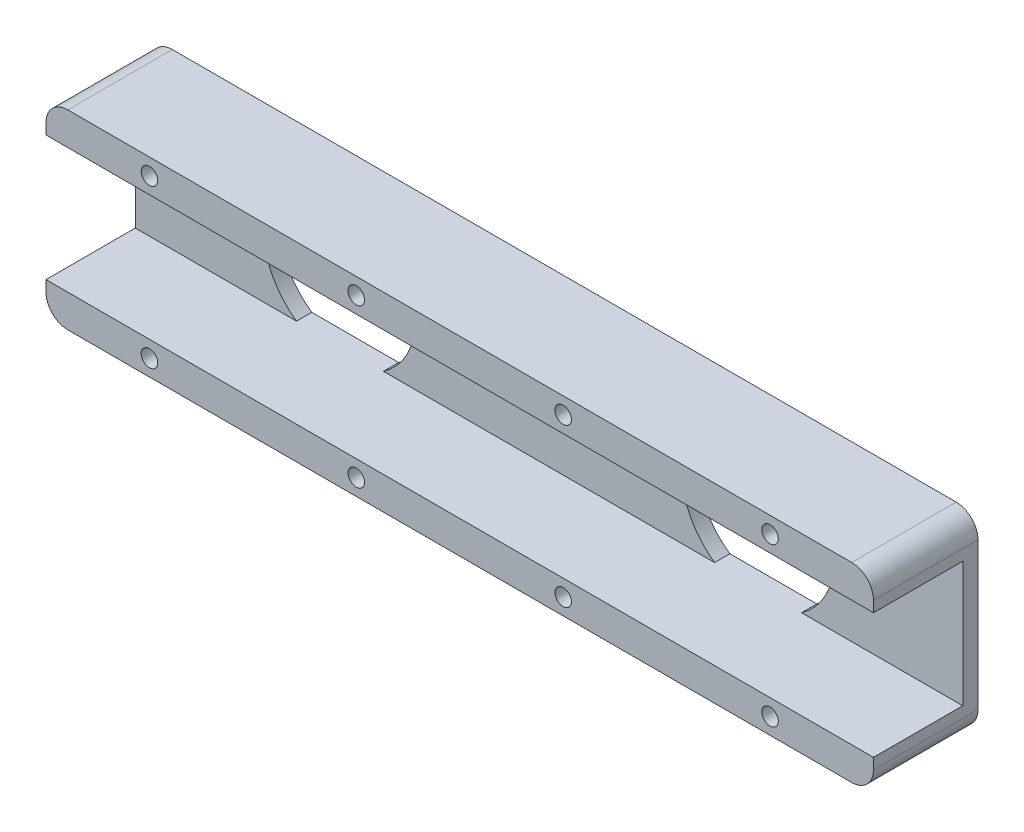
SolidWorks part; units mm, degrees
material "ABS"
ref_plane "Front Plane" through (0, 0, 0) normal (0, 0, 1) x (1, 0, 0)
ref_plane "Top Plane" through (0, 0, 0) normal (0, 1, 0) x (1, 0, 0)
ref_plane "Right Plane" through (0, 0, 0) normal (1, 0, 0) x (0, 0, -1)
sketch "Sketch1" plane through (0, 0, 0) normal (0, 0, 1) x (1, 0, 0)
  line L0 (-95, -14.375) -> (-95, 14.375) construction
  line L1 (-95, -14.375) -> (95, -14.375) construction
  line L2 (-95, 14.375) -> (95, 14.375) construction
  line L3 (95, -14.375) -> (95, 14.375) construction
  line L4 (-95, -14.375) -> (95, 14.375) construction
  line L5 (-95, 14.375) -> (95, -14.375) construction
  line L6 (1, 14.375) -> (1, -14.375) construction
  line L7 (0, 14.375) -> (0, -14.375) construction
  line L8 (-1, 14.375) -> (-1, -14.375) construction
  line L9 (1, 0) -> (95, 0) construction
  line L10 (-1, 0) -> (-95, 0) construction
  line L11 (-95, 14.375) -> (-95, 21.875) construction
  line L12 (-95, 21.875) -> (95, 21.875) construction
  line L13 (95, 21.875) -> (95, 14.375) construction
  line L14 (-95, -14.375) -> (-95, -21.875) construction
  line L15 (95, -21.875) -> (95, -14.375) construction
  line L16 (-95, -21.875) -> (95, -21.875) construction
  line L17 (32.5, -3.375) -> (-61.5, -3.375) construction
  circle A0 centre (48, 0) radius 17.5 construction
  circle A1 centre (-48, 0) radius 17.5 construction
  point P1 (0, 0)
  point P19 (48, 0)
  point P20 (-48, 0)
  point P29 (32.5, -3.375)
  point P30 (-61.5, -3.375)
  dimension "D5" = 35
  dimension "D1" = 28.75
  dimension "D2" = 94
  dimension "D3" = 2
  dimension "D4" = 7.5
  dimension "D6" = 11
  dimension "D7" = 31.5
  dimension "D9" = 94
  dimension "D8" = 2
sketch "Sketch5" plane through (0, 0, 0) normal (0, 0, 1) x (1, 0, 0)
  line L0 (95, 21.875) -> (95, 14.375) construction
  line L5 (95, -14.375) -> (95, 14.375) construction
  line L6 (95, -21.875) -> (95, -14.375) construction
  line L7 (-95, -21.875) -> (95, -21.875) construction
  line L8 (-95, -14.375) -> (-95, -21.875) construction
  line L9 (-95, -14.375) -> (-95, 14.375) construction
  line L10 (-95, 21.875) -> (95, 21.875) construction
  line L11 (-95, 14.375) -> (-95, 21.875) construction
  line L12 (95, 21.875) -> (95, 14.375)
  line L13 (95, -14.375) -> (95, 14.375)
  line L14 (95, -21.875) -> (95, -14.375)
  line L15 (-95, -21.875) -> (95, -21.875)
  line L16 (-95, -14.375) -> (-95, -21.875)
  line L17 (-95, -14.375) -> (-95, 14.375)
  line L18 (-95, 21.875) -> (95, 21.875)
  line L19 (-95, 14.375) -> (-95, 21.875)
  line L20 (0, 14.375) -> (0, -14.375) construction
  line L21 (1, 0) -> (95, 0) construction
  line L22 (-95, 14.375) -> (95, 14.375) construction
  line L23 (-95, -14.375) -> (95, -14.375) construction
  line L24 (57.9804, 14.375) -> (38.0196, 14.375)
  line L25 (57.9804, -14.375) -> (38.0196, -14.375)
  line L26 (-57.9804, -14.375) -> (-38.0196, -14.375)
  line L27 (-57.9804, 14.375) -> (-38.0196, 14.375)
  arc A4 (38.0196, 14.375) -> (38.0196, -14.375) centre (48, 0) ccw
  arc A5 (57.9804, 14.375) -> (57.9804, -14.375) centre (48, 0) cw
  circle A6 centre (48, 0) radius 17.5 construction
  arc A7 (-57.9804, 14.375) -> (-57.9804, -14.375) centre (-48, 0) ccw
  arc A8 (-38.0196, 14.375) -> (-38.0196, -14.375) centre (-48, 0) cw
extrude "Boss-Extrude4" add sketch "Sketch5" along normal blind 3.5
sketch "Sketch6" plane through (0, 0, 3.5) normal (0, 0, 1) x (1, 0, 0)
  line L1 (95, 21.875) -> (-95, 21.875)
  line L2 (95, 21.875) -> (95, 14.375)
  line L3 (95, 14.375) -> (-95, 14.375)
  line L4 (-95, 21.875) -> (-95, 14.375)
  line L5 (95, -14.375) -> (-95, -14.375)
  line L6 (95, -14.375) -> (95, -21.875)
  line L7 (95, -21.875) -> (-95, -21.875)
  line L8 (-95, -14.375) -> (-95, -21.875)
extrude "Boss-Extrude5" add sketch "Sketch6" along normal blind 20.5
sketch "Sketch7" plane through (0, 0, 24) normal (0, 0, 1) x (1, 0, 0)
  line L0 (-95, 18.125) -> (-71.25, 18.125) construction
  line L1 (-95, 14.375) -> (-95, 21.875) construction
  line L2 (-71.25, 18.125) -> (-47.5, 18.125) construction
  line L3 (-47.5, 18.125) -> (-23.75, 18.125) construction
  line L4 (-23.75, 18.125) -> (0, 18.125) construction
  line L5 (0, 18.125) -> (23.75, 18.125) construction
  line L6 (23.75, 18.125) -> (47.5, 18.125) construction
  line L7 (47.5, 18.125) -> (71.25, 18.125) construction
  line L8 (71.25, 18.125) -> (95, 18.125) construction
  line L9 (95, 21.875) -> (95, 14.375) construction
  line L10 (95, 0) -> (-95, 0) construction
  line L11 (71.25, -18.125) -> (95, -18.125) construction
  line L12 (47.5, -18.125) -> (71.25, -18.125) construction
  line L13 (23.75, -18.125) -> (47.5, -18.125) construction
  line L14 (0, -18.125) -> (23.75, -18.125) construction
  line L15 (-23.75, -18.125) -> (0, -18.125) construction
  line L16 (-47.5, -18.125) -> (-23.75, -18.125) construction
  line L17 (-71.25, -18.125) -> (-47.5, -18.125) construction
  line L18 (-95, -18.125) -> (-71.25, -18.125) construction
  point P27 (-71.25, 18.125)
  point P28 (-23.75, 18.125)
  point P29 (23.75, 18.125)
  point P30 (71.25, 18.125)
  point P31 (71.25, -18.125)
  point P32 (23.75, -18.125)
  point P33 (-23.75, -18.125)
  point P34 (-71.25, -18.125)
hole_wizard "CSK for #6 Flat Head Machine Screw1" positions "Sketch8" profile "Sketch10" countersink size "#6" standard "ANSI Inch" end condition through all
sketch "Sketch8" plane through (0, 0, 0) normal (0, 0, -1) x (-1, 0, 0)
  point P0 (71.25, 18.125)
  point P3 (23.75, 18.125)
  point P6 (-23.75, 18.125)
  point P9 (-71.25, 18.125)
  point P12 (71.25, -18.125)
  point P15 (23.75, -18.125)
  point P18 (-23.75, -18.125)
  point P21 (-71.25, -18.125)
sketch "Sketch10" plane through (-71.25, 18.125, 0) normal (1, 0, 0) x (0, 1, 0)
  line L0 (0, 0) -> (0, 24)
  line L1 (0, 24) -> (1.8986, 24)
  line L2 (1.8986, 24) -> (1.8986, 1.892)
  line L3 (1.8986, 1.892) -> (3.5433, 0)
  line L5 (3.5433, 0) -> (0, 0)
  line L6 (-1.8986, 1.892) -> (-3.5433, 0) construction
  line L11 (0, -6.35) -> (0, 107.95) construction
  dimension "Thru Hole Dia." = 3.7973
  dimension "Thru Hole Depth" = 24
  dimension "Near C'Sink Dia." = 7.0866
  dimension "Near C'Sink Angle" = 82
fillet "Fillet1" radius 5 4 edges at (95, 21.875, 12) (95, -21.875, 12) (-95, -21.875, 12) (-95, 21.875, 12)
equation "\"wall_thickness\"= 7.5mm"
equation "\"D4@Sketch1\"=\"wall_thickness\""
equation "\"D1@Boss-Extrude4\"=\"wall_thickness\""
equation "\"D9@Sketch1\"=\"D2@Sketch1\""
